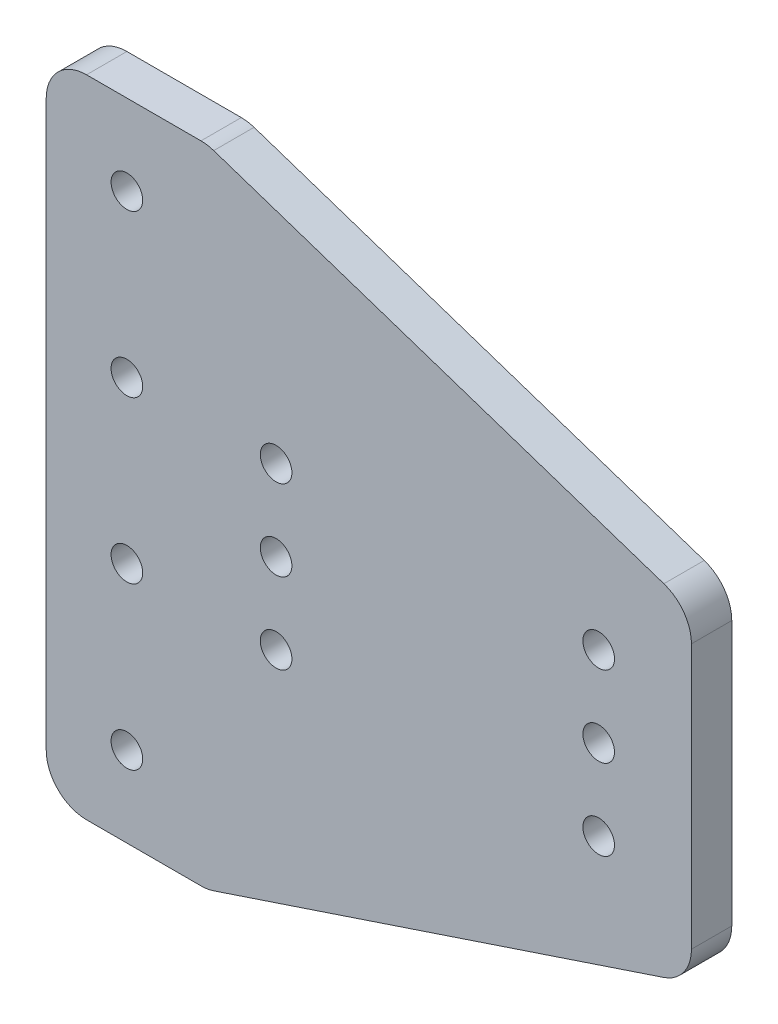
SolidWorks part; units mm, degrees
material "6061-T6 (SS)"
ref_plane "Front Plane" through (0, 0, 0) normal (0, 0, 1) x (1, 0, 0)
ref_plane "Top Plane" through (0, 0, 0) normal (0, 1, 0) x (1, 0, 0)
ref_plane "Right Plane" through (0, 0, 0) normal (1, 0, 0) x (0, 0, -1)
sketch "Sketch1" plane through (0, 0, 0) normal (0, 0, 1) x (1, 0, 0)
  line L0 (36.195, 63.5) -> (86.995, 63.5) construction
  line L1 (0, 0) -> (25.4, 0)
  line L2 (0, 0) -> (0, 101.6)
  line L3 (0, 101.6) -> (25.4, 101.6)
  line L4 (101.6, 25.4) -> (101.6, 76.2)
  line L5 (25.4, 101.6) -> (25.4, 0) construction
  line L6 (25.4, 101.6) -> (101.6, 76.2)
  line L7 (25.4, 0) -> (101.6, 25.4)
  circle A0 centre (36.195, 63.5) radius 2.4892
  circle A1 centre (86.995, 63.5) radius 2.4892
  circle A2 centre (86.995, 50.8) radius 2.4892
  circle A3 centre (86.995, 38.1) radius 2.4892
  circle A4 centre (36.195, 50.8) radius 2.4892
  circle A5 centre (36.195, 38.1) radius 2.4892
  circle A6 centre (12.7, 88.9) radius 2.4892
  circle A7 centre (12.7, 63.5) radius 2.4892
  circle A8 centre (12.7, 38.1) radius 2.4892
  circle A9 centre (12.7, 12.7) radius 2.4892
  point P1 (0, 0)
  point P7 (101.6, 72.8714)
  point P9 (0, 50.8)
  dimension "D7" = 4.9784
  dimension "D11" = 12.7
  dimension ".196" = 4.9784
  dimension "D1" = 101.6
  dimension "D2" = 101.6
  dimension "D5" = 50.8
  dimension "D6" = 12.7
  dimension "D8" = 36.195
  dimension "D10" = 25.4
  dimension "D12" = 12.7
  dimension "D13" = 25.4
  dimension "D14" = 50.8
  dimension "D3" = 2
  dimension "D4" = 3
  dimension "D9" = 4
extrude "Boss-Extrude1" add sketch "Sketch1" along normal blind 6.35
fillet "Fillet1" radius 6.35 6 edges at (0, 0, 3.175) (0, 101.6, 3.175) (25.4, 101.6, 3.175) (101.6, 25.4, 3.175) (25.4, 0, 3.175) (101.6, 76.2, 3.175)
